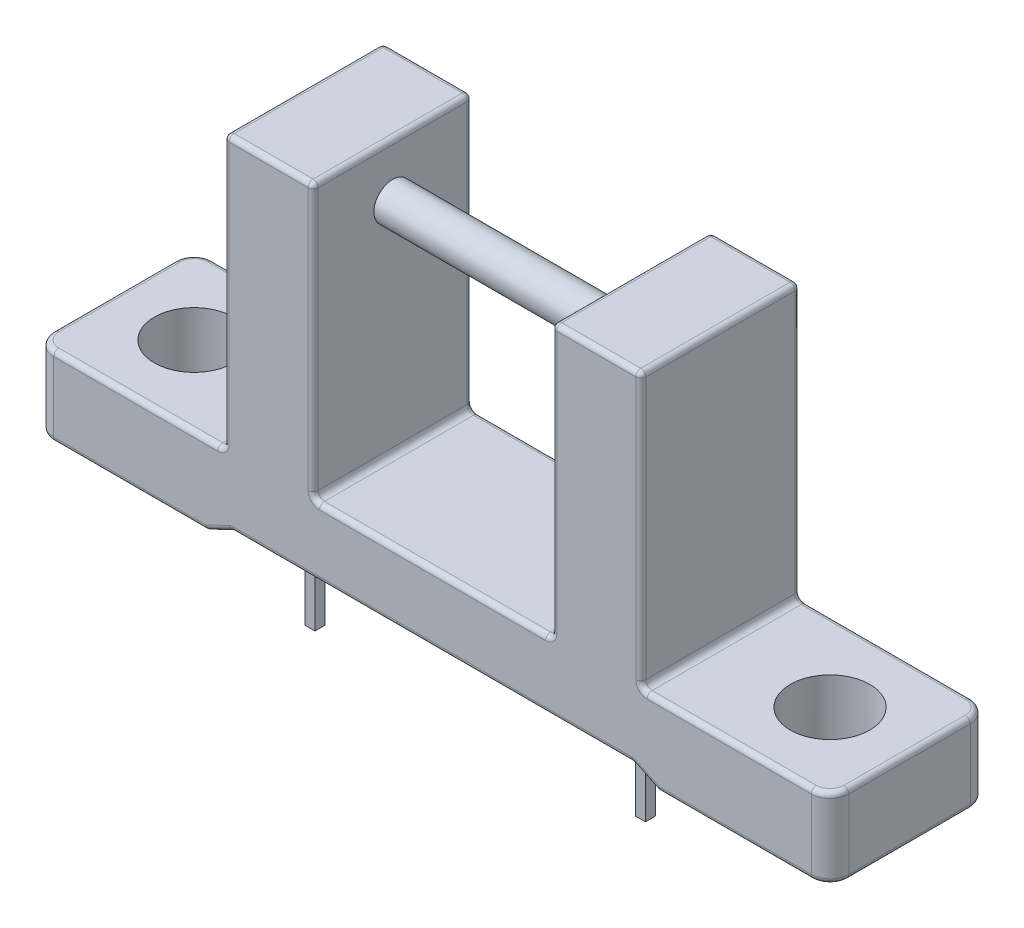
SolidWorks part; units mm, degrees
ref_plane "Front Plane" through (0, 0, 0) normal (0, 0, 1) x (1, 0, 0)
ref_plane "Top Plane" through (0, 0, 0) normal (0, 1, 0) x (1, 0, 0)
ref_plane "Right Plane" through (0, 0, 0) normal (1, 0, 0) x (0, 0, -1)
sketch "Croquis1" plane through (0, 0, 0) normal (0, 0, 1) x (1, 0, 0)
  line L0 (-8, 0.48) -> (8, 0.48)
  line L1 (8, 0.48) -> (9, 0)
  line L2 (9, 0) -> (15.875, 0)
  line L3 (15.875, 0) -> (15.875, 3.18)
  line L4 (15.875, 3.18) -> (8.32, 3.18)
  line L5 (8.32, 3.18) -> (8.32, 14.1)
  line L6 (8.32, 14.1) -> (4.765, 14.1)
  line L7 (4.765, 14.1) -> (4.765, 3.18)
  line L8 (4.765, 3.18) -> (-4.765, 3.18)
  line L9 (0, 3.18) -> (0, 0.48) construction
  line L10 (-8, 0.48) -> (-9, 0)
  line L11 (-9, 0) -> (-15.875, 0)
  line L12 (-15.875, 0) -> (-15.875, 3.18)
  line L13 (-15.875, 3.18) -> (-8.32, 3.18)
  line L14 (-8.32, 3.18) -> (-8.32, 14.1)
  line L15 (-8.32, 14.1) -> (-4.765, 14.1)
  line L16 (-4.765, 14.1) -> (-4.765, 3.18)
  point P5 (0, 0)
  point P12 (9.761, 0)
  dimension "D1" = 16
  dimension "D2" = 31.75
  dimension "D3" = 16.64
  dimension "D4" = 9.53
  dimension "D5" = 3.18
  dimension "D6" = 2.7
  dimension "D7" = 14.1
  dimension "D8" = 1
extrude "Saliente-Extruir1" add sketch "Croquis1" along normal mid plane 6.35 contours L6 L7 L8 L16 L15 L14 L13 L12 L11 L10 L0 L1 L2 L3 L4 L5
fillet "Redondeo1" radius 0.25 4 edges at (8.32, 3.18, 0) (4.765, 3.18, 0) (-4.765, 3.18, 0) (-8.32, 3.18, 0)
fillet "Redondeo2" radius 0.75 4 edges at (-15.875, 1.59, -3.175) (15.875, 1.59, -3.175) (15.875, 1.59, 3.175) (-15.875, 1.59, 3.175)
fillet "Redondeo3" radius 0.2 56 edges at (-8.5, 0.24, -3.175) (8.5, 0.24, -3.175) (-12.0625, 0, -3.175) (-15.6553, 0, -2.9553) (-15.875, 0, 0) (-15.6553, 0, 2.9553) (-8.32, 8.765, -3.175) (-8.3932, 3.2532, -3.175) (-11.8475, 3.18, -3.175) (-15.6553, 3.18, -2.9553) (-15.875, 3.18, 0) (-15.6553, 3.18, 2.9553) (8.32, 8.765, -3.175) (8.3932, 3.2532, -3.175) (11.8475, 3.18, -3.175) (15.6553, 3.18, -2.9553) (15.875, 3.18, 0) (15.6553, 3.18, 2.9553) (12.0625, 0, -3.175) (15.6553, 0, -2.9553) (15.875, 0, 0) (15.6553, 0, 2.9553) (4.765, 8.765, -3.175) (4.6918, 3.2532, -3.175) (0, 3.18, -3.175) (-4.6918, 3.2532, -3.175) (-8, 0.48, 0) (8, 0.48, 0) (0, 0.48, -3.175) (8.5, 0.24, 3.175) (0, 0.48, 3.175) (-8.5, 0.24, 3.175) (-12.0625, 0, 3.175) (-11.8475, 3.18, 3.175) (-8.3932, 3.2532, 3.175) (-8.32, 8.765, 3.175) (-6.5425, 14.1, 3.175) (-4.765, 8.765, 3.175) (-4.6918, 3.2532, 3.175) (0, 3.18, 3.175) (4.6918, 3.2532, 3.175) (4.765, 8.765, 3.175) (6.5425, 14.1, 3.175) (8.32, 8.765, 3.175) (8.3932, 3.2532, 3.175) (11.8475, 3.18, 3.175) (12.0625, 0, 3.175) (9, 0, 0) (-9, 0, 0) (-4.765, 8.765, -3.175) (8.32, 14.1, 0) (4.765, 14.1, 0) (6.5425, 14.1, -3.175) (-8.32, 14.1, 0) (-6.5425, 14.1, -3.175) (-4.765, 14.1, 0)
sketch "Croquis2" plane through (0, 0, 0) normal (1, 0, 0) x (0, 0, -1)
  line L3 (-2.975, 14.1) -> (2.975, 14.1) construction
  circle A0 centre (0, 11.95) radius 0.75
  point P2 (0, 0)
  point P5 (0, 0)
  point P6 (0.8554, 11.95)
  point P7 (0, 0)
  point P8 (0, 0)
  dimension "D2" = 1.5
  dimension "D1" = 2.15
extrude "Saliente-Extruir2" add sketch "Croquis2" along normal up to next and the other way up to next
sketch "Croquis3" plane through (0, 0, 0) normal (0, -1, 0) x (1, 0, 0)
  line L0 (0, -3.4925) -> (0, 3.4925) construction
  line L1 (-6.8, 1.47) -> (-6.4, 1.47)
  line L2 (-6.8, 1.47) -> (-6.8, 1.07)
  line L3 (-6.8, 1.07) -> (-6.4, 1.07)
  line L4 (-6.4, 1.47) -> (-6.4, 1.07)
  line L5 (6.8, 1.47) -> (6.8, 1.07)
  line L6 (6.8, 1.07) -> (6.4, 1.07)
  line L7 (6.4, 1.47) -> (6.4, 1.07)
  line L8 (6.8, 1.47) -> (6.4, 1.47)
  line L9 (7.755, 0) -> (-7.755, 0) construction
  line L10 (6.8, -1.47) -> (6.4, -1.47)
  line L11 (6.4, -1.47) -> (6.4, -1.07)
  line L12 (6.8, -1.07) -> (6.4, -1.07)
  line L13 (6.8, -1.47) -> (6.8, -1.07)
  line L14 (-6.4, -1.47) -> (-6.4, -1.07)
  line L15 (-6.8, -1.07) -> (-6.4, -1.07)
  line L16 (-6.8, -1.47) -> (-6.8, -1.07)
  line L17 (-6.8, -1.47) -> (-6.4, -1.47)
  point P4 (-6.4, 1.27)
  point P5 (-6.6, 1.47)
  dimension "D1" = 0.4
  dimension "D2" = 0.4
  dimension "D3" = 1.27
  dimension "D4" = 6.6
extrude "Saliente-Extruir3" add sketch "Croquis3" along normal blind 3 and the other way up to next
sketch "Croquis4" plane through (0, 3.18, 0) normal (0, 1, 0) x (1, 0, 0)
  line L0 (0, -3.4925) -> (0, 3.4925) construction
  circle A0 centre (-12.7, 0) radius 1.585
  circle A1 centre (12.7, 0) radius 1.585
  point P2 (0, 0)
  dimension "D1" = 3.17
  dimension "D2" = 12.7
extrude "Cortar-Extruir1" cut sketch "Croquis4" against normal through all
equation "\"D1@Croquis2\"=1.40mm+\"D2@Croquis2\"/2"
